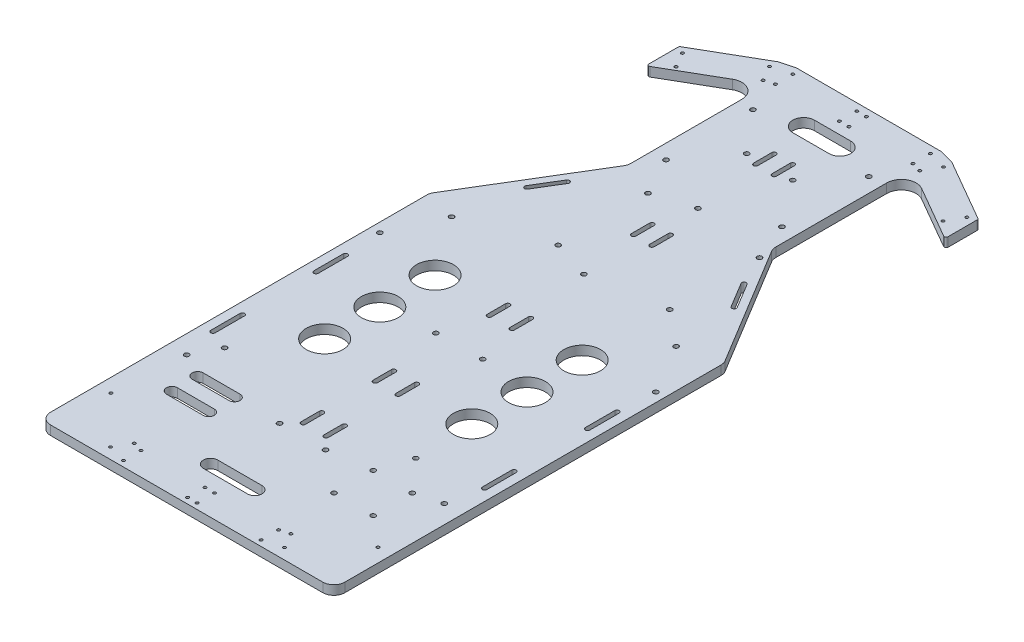
SolidWorks part; units mm, degrees
ref_plane "Front Plane" through (0, 0, 0) normal (0, 0, 1) x (1, 0, 0)
ref_plane "Top Plane" through (0, 0, 0) normal (0, 1, 0) x (1, 0, 0)
ref_plane "Right Plane" through (0, 0, 0) normal (1, 0, 0) x (0, 0, -1)
sketch "Sketch1" plane through (0, 0, 0) normal (0, 1, 0) x (1, 0, 0)
  line L0 (-3.559, 334.4007) -> (-3.559, -135.4993) construction
  line L1 (-53.658, 335.4416) -> (46.4133, 335.4416)
  line L2 (46.4133, 335.4416) -> (56.4133, 332.7622)
  line L3 (-105.159, -135.4993) -> (98.041, -135.4993)
  line L4 (99.7145, 307.7622) -> (99.7145, 284.6681)
  line L5 (-19.434, -135.4993) -> (-19.434, -55.4993) construction
  line L6 (-19.434, -55.4993) -> (12.316, -55.4993) construction
  line L7 (12.316, -55.4993) -> (12.316, -135.4993) construction
  line L8 (-19.434, -55.4993) -> (-19.434, 267.0007) construction
  line L9 (12.316, -55.4993) -> (12.316, 267.0007) construction
  line L10 (-53.5312, 315.4416) -> (-53.5312, 335.4416) construction
  line L11 (41.041, -51.3493) -> (68.041, -51.3493) construction
  line L12 (41.041, -51.3493) -> (41.041, -78.3493) construction
  line L13 (41.041, -78.3493) -> (68.041, -78.3493) construction
  line L14 (68.041, -51.3493) -> (68.041, -78.3493) construction
  line L15 (-92.459, -46.5993) -> (98.0409, -46.5993) construction
  line L16 (84.2181, -36.1058) -> (84.2181, 133.8942) construction
  line L17 (98.041, 133.8942) -> (-105.159, 133.8942) construction
  line L18 (48.441, -29.3238) -> (-83.559, -29.3238) construction
  line L19 (99.7145, 284.6681) -> (46.4133, 315.4416)
  line L20 (-0.259, 335.4416) -> (-0.259, 315.4416) construction
  line L21 (-106.8325, 307.7622) -> (-106.8325, 284.6681)
  line L22 (-53.5867, 219.1052) -> (-53.5867, 411.7781) construction
  line L23 (46.4133, 315.4416) -> (56.4133, 332.7622) construction
  line L24 (-105.159, 133.8942) -> (-53.5867, 219.1052)
  line L25 (46.4133, 219.1052) -> (98.041, 133.8942)
  line L26 (46.4133, 219.1052) -> (46.4133, 315.4416) construction
  line L27 (-83.559, -29.3238) -> (-83.559, 127.3942) construction
  line L28 (-75.3023, 127.3942) -> (-75.3023, 133.8942) construction
  line L29 (56.4133, 332.7622) -> (99.7145, 307.7622)
  line L30 (-83.559, 127.3942) -> (71.441, 127.3942) construction
  line L32 (-53.5312, 315.4416) -> (-63.5312, 332.7622) construction
  line L33 (-53.5312, 335.4416) -> (-63.5312, 332.7622)
  line L34 (-26.8485, 52.9803) -> (30.8308, 52.9803) construction
  line L35 (-63.5312, 332.7622) -> (-106.8325, 307.7622)
  line L36 (-105.159, 133.8942) -> (-105.159, -135.4993)
  line L37 (-6.859, 335.4416) -> (-6.859, 315.4416) construction
  line L38 (23.5928, 224.6027) -> (12.316, 224.6027) construction
  line L39 (-53.5312, 330.4416) -> (46.4133, 330.4416) construction
  line L40 (-29.8184, 209.2254) -> (-29.8184, 147.2254) construction
  line L41 (-29.8184, 147.2254) -> (47.1816, 147.2254) construction
  line L42 (47.1816, 147.2254) -> (47.1816, 209.2254) construction
  line L43 (-29.8184, 209.2254) -> (47.1816, 209.2254) construction
  line L44 (-53.5867, 219.1052) -> (46.4133, 219.1052) construction
  line L45 (-105.1532, 315.4416) -> (98.0468, 315.4416) construction
  line L46 (-53.658, 315.4416) -> (-53.658, 305.4416) construction
  line L47 (-53.5867, 305.4416) -> (46.4133, 305.4416) construction
  line L48 (-53.5867, 284.8828) -> (-43.5867, 284.8828) construction
  line L49 (-53.5312, 318.4416) -> (46.4133, 318.4416) construction
  line L50 (46.4133, 284.8828) -> (36.4133, 284.8828) construction
  line L51 (-51.0312, 335.4416) -> (-51.0312, 315.4416) construction
  line L52 (-53.5867, 219.1052) -> (-53.5867, 315.4416)
  line L53 (46.4133, 315.4416) -> (46.4133, 219.1052)
  line L54 (-53.658, 315.4416) -> (-53.658, 335.4416) construction
  line L55 (46.4133, 315.4416) -> (46.4133, 335.4416) construction
  line L56 (43.9133, 335.4416) -> (43.9133, 315.4416) construction
  line L57 (-105.159, 99.4507) -> (98.041, 99.4507) construction
  line L58 (-16.059, 302.9416) -> (8.941, 302.9416) construction
  line L59 (-16.059, 310.4416) -> (8.941, 310.4416)
  line L60 (-16.059, 295.4416) -> (8.941, 295.4416)
  line L61 (-9.923, 263.6917) -> (-9.909, 276.3916) construction
  line L62 (-11.423, 263.6933) -> (-11.409, 276.3933)
  line L63 (-8.423, 263.69) -> (-8.409, 276.39)
  line L64 (2.805, 263.6917) -> (2.791, 276.3916) construction
  line L65 (4.305, 263.6933) -> (4.291, 276.3933)
  line L66 (1.305, 263.69) -> (1.291, 276.39)
  line L67 (-11.433, 81.3437) -> (-11.433, 94.0437) construction
  line L68 (98.041, 133.8942) -> (98.041, -135.4993)
  line L69 (-12.957, 81.3437) -> (-12.957, 94.0437)
  line L70 (-9.909, 81.3437) -> (-9.909, 94.0437)
  line L71 (-9.909, 179.3877) -> (-9.909, 192.0877) construction
  line L72 (-11.433, 179.3877) -> (-11.433, 192.0877)
  line L73 (-8.385, 179.3877) -> (-8.385, 192.0877)
  line L74 (-11.433, 2.6037) -> (-11.433, 15.3037) construction
  line L75 (-12.957, 2.6037) -> (-12.957, 15.3037)
  line L76 (-9.909, 2.6037) -> (-9.909, 15.3037)
  line L77 (-11.433, -47.1803) -> (-11.433, -34.4803) construction
  line L78 (-12.957, -47.1803) -> (-12.957, -34.4803)
  line L79 (-9.909, -47.1803) -> (-9.909, -34.4803)
  line L80 (-97.285, 47.5342) -> (-97.285, 67.8542) construction
  line L81 (-98.809, 47.5342) -> (-98.809, 67.8542)
  line L82 (-95.761, 47.5342) -> (-95.761, 67.8542)
  line L83 (-18.799, -103.7493) -> (11.681, -103.7493) construction
  line L84 (-18.799, -98.7493) -> (11.681, -98.7493)
  line L85 (-18.799, -108.7493) -> (11.681, -108.7493)
  line L86 (4.315, -47.1803) -> (4.315, -34.4803) construction
  line L87 (5.839, -47.1803) -> (5.839, -34.4803)
  line L88 (2.791, -47.1803) -> (2.791, -34.4803)
  line L89 (4.315, 2.6037) -> (4.315, 15.3037) construction
  line L90 (5.839, 2.6037) -> (5.839, 15.3037)
  line L91 (2.791, 2.6037) -> (2.791, 15.3037)
  line L92 (4.315, 81.3437) -> (4.315, 94.0437) construction
  line L93 (5.839, 81.3437) -> (5.839, 94.0437)
  line L94 (2.791, 81.3437) -> (2.791, 94.0437)
  line L95 (2.791, 179.3877) -> (2.791, 192.0877) construction
  line L96 (4.315, 179.3877) -> (4.315, 192.0877)
  line L97 (1.267, 179.3877) -> (1.267, 192.0877)
  line L98 (-53.5867, 315.4416) -> (-106.8325, 284.6681)
  line L101 (-75.1227, 170.9222) -> (-64.6014, 188.3062) construction
  line L102 (-76.4265, 171.7113) -> (-65.9052, 189.0953)
  line L103 (-73.8189, 170.1331) -> (-63.2976, 187.5171)
  line L104 (68.0048, 170.9222) -> (57.4834, 188.3062) construction
  line L105 (69.3086, 171.7113) -> (58.7872, 189.0953)
  line L106 (66.701, 170.1331) -> (56.1796, 187.5171)
  line L110 (-75.949, -55.4893) -> (-50.549, -55.4893) construction
  line L111 (-75.949, -51.6793) -> (-50.549, -51.6793)
  line L112 (-75.949, -59.2993) -> (-50.549, -59.2993)
  line L113 (-75.949, -73.2693) -> (-50.549, -73.2693) construction
  line L114 (-75.949, -69.4593) -> (-50.549, -69.4593)
  line L115 (-75.949, -77.0793) -> (-50.549, -77.0793)
  line L116 (-97.285, -23.5858) -> (-97.285, -3.2658) construction
  line L117 (-98.809, -23.5858) -> (-98.809, -3.2658)
  line L118 (-95.761, -23.5858) -> (-95.761, -3.2658)
  line L119 (90.167, -23.5858) -> (90.167, -3.2658) construction
  line L120 (91.691, -23.5858) -> (91.691, -3.2658)
  line L121 (88.643, -23.5858) -> (88.643, -3.2658)
  line L122 (90.167, 47.5342) -> (90.167, 67.8542) construction
  line L123 (91.691, 47.5342) -> (91.691, 67.8542)
  line L124 (88.643, 47.5342) -> (88.643, 67.8542)
  circle A0 centre (-92.459, -46.5993) radius 1.651
  circle A1 centre (-19.434, -55.4993) radius 1.651
  circle A2 centre (12.316, -55.4993) radius 1.651
  circle A3 centre (-19.434, 267.0007) radius 1.651
  circle A4 centre (12.316, 267.0007) radius 1.651
  circle A5 centre (41.041, -51.3493) radius 1.651
  circle A6 centre (41.041, -78.3493) radius 1.651
  circle A7 centre (68.041, -78.3493) radius 1.651
  circle A8 centre (68.041, -51.3493) radius 1.651
  circle A9 centre (48.441, -29.3238) radius 1.651
  circle A10 centre (-83.559, -29.3238) radius 1.651
  circle A11 centre (-98.809, 93.1007) radius 1.651
  circle A12 centre (-3.559, 138.7138) radius 1.651
  circle A13 centre (-83.559, 127.3942) radius 1.651
  circle A14 centre (71.441, 127.3942) radius 1.651
  circle A15 centre (-19.434, 52.3942) radius 1.651
  circle A16 centre (12.316, 52.9803) radius 1.651
  circle A17 centre (91.6909, 93.1007) radius 1.651
  circle A18 centre (-29.8184, 209.2254) radius 1.651
  circle A19 centre (-29.8184, 147.2254) radius 1.651
  circle A20 centre (47.1816, 147.2254) radius 1.651
  circle A21 centre (47.1816, 209.2254) radius 1.651
  circle A22 centre (-43.5809, 295.4416) radius 1.651
  circle A23 centre (36.4191, 295.4416) radius 1.651
  circle A24 centre (-43.5532, 235.4416) radius 1.651
  circle A25 centre (36.441, 235.4416) radius 1.651
  circle A26 centre (85.341, -46.5993) radius 1.651
  circle A27 centre (-51.0312, 330.4416) radius 1
  circle A28 centre (-51.0312, 318.4416) radius 1
  circle A29 centre (43.9191, 330.4416) radius 1
  circle A30 centre (43.9133, 318.4416) radius 1
  circle A31 centre (-6.859, 330.4416) radius 1
  circle A32 centre (-0.259, 330.4416) radius 1
  circle A33 centre (-6.859, 318.4416) radius 1
  circle A34 centre (-0.259, 318.4416) radius 1
  circle A35 centre (56.5114, 326.932) radius 1
  circle A36 centre (50.5114, 316.5397) radius 1
  circle A37 centre (94.6165, 304.932) radius 1
  circle A38 centre (88.6165, 294.5397) radius 1
  circle A39 centre (-95.7344, 294.5397) radius 1
  circle A40 centre (-57.6293, 316.5397) radius 1
  circle A41 centre (-63.6293, 326.932) radius 1
  circle A42 centre (-101.7344, 304.932) radius 1
  circle A43 centre (88.6165, -95.6383) radius 1
  circle A44 centre (-54.359, 86.7507) radius 12.7
  circle A45 centre (50.5114, -117.6383) radius 1
  circle A46 centre (56.5114, -128.0307) radius 1
  circle A47 centre (-95.7344, -95.6383) radius 1
  circle A48 centre (-54.359, 48.6507) radius 12.7
  circle A49 centre (-57.6293, -117.6383) radius 1
  circle A50 centre (-63.6293, -128.0307) radius 1
  circle A51 centre (43.9133, -119.5403) radius 1
  circle A52 centre (43.9191, -131.5403) radius 1
  circle A53 centre (-0.259, -119.5403) radius 1
  circle A54 centre (-0.259, -131.5403) radius 1
  circle A55 centre (-6.859, -119.5403) radius 1
  circle A56 centre (-6.859, -131.5403) radius 1
  circle A57 centre (-51.0312, -119.5403) radius 1
  circle A58 centre (-51.0312, -131.5403) radius 1
  arc A59 (-16.059, 310.4416) -> (-16.059, 295.4416) centre (-16.059, 302.9416) ccw
  arc A60 (8.941, 295.4416) -> (8.941, 310.4416) centre (8.941, 302.9416) ccw
  arc A61 (-11.423, 263.6933) -> (-8.423, 263.69) centre (-9.923, 263.6917) ccw
  arc A62 (-8.409, 276.39) -> (-11.409, 276.3933) centre (-9.909, 276.3916) ccw
  arc A63 (4.305, 263.6933) -> (1.305, 263.69) centre (2.805, 263.6917) cw
  arc A64 (1.291, 276.39) -> (4.291, 276.3933) centre (2.791, 276.3916) cw
  arc A65 (-12.957, 81.3437) -> (-9.909, 81.3437) centre (-11.433, 81.3437) ccw
  arc A66 (-9.909, 94.0437) -> (-12.957, 94.0437) centre (-11.433, 94.0437) ccw
  arc A67 (-11.433, 179.3877) -> (-8.385, 179.3877) centre (-9.909, 179.3877) ccw
  arc A68 (-8.385, 192.0877) -> (-11.433, 192.0877) centre (-9.909, 192.0877) ccw
  arc A69 (-12.957, 2.6037) -> (-9.909, 2.6037) centre (-11.433, 2.6037) ccw
  arc A70 (-9.909, 15.3037) -> (-12.957, 15.3037) centre (-11.433, 15.3037) ccw
  arc A71 (-12.957, -47.1803) -> (-9.909, -47.1803) centre (-11.433, -47.1803) ccw
  arc A72 (-9.909, -34.4803) -> (-12.957, -34.4803) centre (-11.433, -34.4803) ccw
  circle A73 centre (-54.359, 10.5507) radius 12.7
  circle A74 centre (47.241, 10.5507) radius 12.7
  arc A75 (-18.799, -98.7493) -> (-18.799, -108.7493) centre (-18.799, -103.7493) ccw
  arc A76 (11.681, -108.7493) -> (11.681, -98.7493) centre (11.681, -103.7493) ccw
  arc A77 (5.839, -47.1803) -> (2.791, -47.1803) centre (4.315, -47.1803) cw
  arc A78 (2.791, -34.4803) -> (5.839, -34.4803) centre (4.315, -34.4803) cw
  arc A79 (5.839, 2.6037) -> (2.791, 2.6037) centre (4.315, 2.6037) cw
  arc A80 (2.791, 15.3037) -> (5.839, 15.3037) centre (4.315, 15.3037) cw
  arc A81 (5.839, 81.3437) -> (2.791, 81.3437) centre (4.315, 81.3437) cw
  arc A82 (2.791, 94.0437) -> (5.839, 94.0437) centre (4.315, 94.0437) cw
  arc A83 (4.315, 179.3877) -> (1.267, 179.3877) centre (2.791, 179.3877) cw
  arc A84 (1.267, 192.0877) -> (4.315, 192.0877) centre (2.791, 192.0877) cw
  circle A85 centre (-3.559, 217.4538) radius 1.651
  arc A87 (-76.4265, 171.7113) -> (-73.8189, 170.1331) centre (-75.1227, 170.9222) ccw
  arc A88 (-63.2976, 187.5171) -> (-65.9052, 189.0953) centre (-64.6014, 188.3062) ccw
  arc A89 (69.3086, 171.7113) -> (66.701, 170.1331) centre (68.0048, 170.9222) cw
  arc A90 (56.1796, 187.5171) -> (58.7872, 189.0953) centre (57.4834, 188.3062) cw
  arc A93 (-75.949, -51.6793) -> (-75.949, -59.2993) centre (-75.949, -55.4893) ccw
  arc A94 (-50.549, -59.2993) -> (-50.549, -51.6793) centre (-50.549, -55.4893) ccw
  arc A95 (-75.949, -69.4593) -> (-75.949, -77.0793) centre (-75.949, -73.2693) ccw
  arc A96 (-50.549, -77.0793) -> (-50.549, -69.4593) centre (-50.549, -73.2693) ccw
  circle A97 centre (47.241, 48.6507) radius 12.7
  circle A98 centre (47.241, 86.7507) radius 12.7
  arc A99 (-98.809, 47.5342) -> (-95.761, 47.5342) centre (-97.285, 47.5342) ccw
  arc A100 (-95.761, 67.8542) -> (-98.809, 67.8542) centre (-97.285, 67.8542) ccw
  arc A101 (-98.809, -23.5858) -> (-95.761, -23.5858) centre (-97.285, -23.5858) ccw
  arc A102 (-95.761, -3.2658) -> (-98.809, -3.2658) centre (-97.285, -3.2658) ccw
  arc A103 (91.691, -23.5858) -> (88.643, -23.5858) centre (90.167, -23.5858) cw
  arc A104 (88.643, -3.2658) -> (91.691, -3.2658) centre (90.167, -3.2658) cw
  arc A105 (91.691, 47.5342) -> (88.643, 47.5342) centre (90.167, 47.5342) cw
  arc A106 (88.643, 67.8542) -> (91.691, 67.8542) centre (90.167, 67.8542) cw
  point P50 (-0.9865, 223.8799)
  point P124 (-101.7344, 304.932)
  point P177 (-3.559, 302.9416)
  point P182 (-9.916, 270.0416)
  point P193 (2.798, 270.0416)
  point P199 (-11.433, 87.6937)
  point P206 (-9.909, 185.7377)
  point P213 (-11.433, 8.9537)
  point P220 (-11.433, -40.8303)
  point P236 (-3.559, -103.7493)
  point P241 (-9.909, 193.6117)
  point P242 (-9.9246, 262.1917)
  point P243 (-11.433, 95.5677)
  point P244 (-11.433, -32.9563)
  point P248 (4.315, -40.8303)
  point P255 (4.315, 8.9537)
  point P262 (4.315, 87.6937)
  point P269 (2.791, 185.7377)
  point P278 (-69.862, 179.6142)
  point P287 (62.7441, 179.6142)
  point P301 (-63.249, -55.4893)
  point P308 (-63.249, -73.2693)
  point P313 (-63.249, -59.2993)
  point P314 (-79.759, -73.2693)
  point P315 (-79.759, -55.4893)
  point P317 (-97.285, 57.6942)
  point P324 (-97.285, -13.4258)
  point P333 (90.167, -13.4258)
  point P340 (90.167, 57.6942)
  dimension "D3" = 3.302
  dimension "D10" = 3.302
  dimension "D11" = 3.302
  dimension "D14" = 3.302
  dimension "D15" = 3.302
  dimension "D20" = 3.302
  dimension "D21" = 3.302
  dimension "D22" = 3.302
  dimension "D23" = 3.302
  dimension "D26" = 3.302
  dimension "D27" = 75
  dimension "D30" = 3.302
  dimension "D32" = 3.302
  dimension "D33" = 60
  dimension "D34" = 3.302
  dimension "D35" = 9.8798
  dimension "D39" = 3.302
  dimension "D43" = 3.302
  dimension "D41" = 3.302
  dimension "D44" = 3.302
  dimension "D45" = 3.302
  dimension "D48" = 3.302
  dimension "D49" = 30
  dimension "D52" = 3.302
  dimension "D54" = 3.302
  dimension "D56" = 3.302
  dimension "D58" = 3.302
  dimension "D62" = 3.302
  dimension "D63" = 10
  dimension "D65" = 3.302
  dimension "D66" = 3.302
  dimension "D67" = 3.302
  dimension "D69" = 100.0713
  dimension "D68" = 469.9
  dimension "D75" = 15.875
  dimension "D77" = 26.2595
  dimension "D47" = 0
  dimension "D50" = 274.2131
  dimension "D51" = 139.7
  dimension "D28" = 139.7
  dimension "D46" = 12.7
  dimension "D57" = 88.9
  dimension "D78" = 60
  dimension "D72" = 10
  dimension "D73" = 10
  dimension "D74" = 60
  dimension "D79" = 9.9722
  dimension "D80" = 3.3
  dimension "D88" = 2
  dimension "D89" = 2
  dimension "D90" = 2
  dimension "D91" = 2
  dimension "D92" = 2
  dimension "D93" = 2
  dimension "D94" = 2
  dimension "D95" = 2
  dimension "D97" = 12.5
  dimension "D98" = 44.1722
  dimension "D100" = 2
  dimension "D101" = 2
  dimension "D102" = 2
  dimension "D103" = 2
  dimension "D104" = 25
  dimension "D118" = 3.048
  dimension "D124" = 66.04
  dimension "D126" = 3.048
  dimension "D140" = 25.4
  dimension "D145" = 50.8
  dimension "D146" = 269.3935
  dimension "D147" = 50.8
  dimension "D149" = 5
  dimension "D151" = 3
  dimension "D152" = 3
  dimension "D153" = 44
  dimension "D154" = 44
  dimension "D148" = 50.8
  dimension "D157" = 25.4
  dimension "D158" = 25.4
  dimension "D159" = 25.4
  dimension "D36" = 3.302
  dimension "D136" = 78.74
  dimension "D1" = 203.2
  dimension "D4" = 88.9
  dimension "D8" = 80
  dimension "D9" = 80
  dimension "D12" = 322.5
  dimension "D13" = 322.5
  dimension "D16" = 57.15
  dimension "D17" = 27
  dimension "D18" = 50
  dimension "D19" = 27
  dimension "D24" = 6.5
  dimension "D25" = 170
  dimension "D29" = 132
  dimension "D31" = 3.3
  dimension "D37" = 100
  dimension "D38" = 156.718
  dimension "D40" = 6.5
  dimension "D42" = 155
  dimension "D53" = 62
  dimension "D55" = 77
  dimension "D59" = 10
  dimension "D60" = 20
  dimension "D61" = 10
  dimension "D64" = 10
  dimension "D70" = 20
  dimension "D71" = 234.95
  dimension "D76" = 15.875
  dimension "D81" = 12.6999
  dimension "D82" = 6.3501
  dimension "D83" = 30.0001
  dimension "D84" = 5
  dimension "D85" = 3
  dimension "D86" = 2.5
  dimension "D87" = 2.5
  dimension "D96" = 25
  dimension "D99" = 15
  dimension "D105" = 12.7
  dimension "D106" = 6.35
  dimension "D107" = 3
  dimension "D108" = 25.4
  dimension "D109" = 31.75
  dimension "D110" = 10
  dimension "D111" = 15.24
  dimension "D112" = 30.48
  dimension "D113" = 6.35
  dimension "D114" = 3.048
  dimension "D115" = 12.7
  dimension "D116" = 68.58
  dimension "D117" = 6.35
  dimension "D119" = 12.7
  dimension "D120" = 83.82
  dimension "D121" = 6.35
  dimension "D122" = 3.048
  dimension "D123" = 12.7
  dimension "D125" = 6.35
  dimension "D127" = 12.7
  dimension "D128" = 35.56
  dimension "D129" = 5
  dimension "D130" = 203.2
  dimension "D131" = 96.3364
  dimension "D132" = 3.048
  dimension "D133" = 20.32
  dimension "D134" = 96.3364
  dimension "D135" = 45.72
  dimension "D137" = 7.62
  dimension "D138" = 7.62
  dimension "D139" = 10.16
  dimension "D141" = 25.4
  dimension "D142" = 25.4
  dimension "D143" = 25.4
  dimension "D144" = 58.42
  dimension "D150" = 5
  dimension "D155" = 3
  dimension "D156" = 3
  dimension "D160" = 12.7
  dimension "D161" = 38.1
  dimension "D162" = 38.1
  dimension "D163" = 76.2
  dimension "D164" = 20.32
  dimension "D165" = 3.048
  dimension "D166" = 6.35
  dimension "D167" = 3.048
  dimension "D168" = 6.35
  dimension "D169" = 20.32
  dimension "D170" = 71.12
extrude "Boss-Extrude1" add sketch "Sketch1" along normal blind 6.35
fillet "Fillet1" radius 7.62 6 edges at (98.041, 3.175, 135.4993) (-105.159, 3.175, 135.4993) (-105.159, 3.175, -133.8942) (98.041, 3.175, -133.8942) (46.4133, 3.175, -219.1052) (-53.5867, 3.175, -219.1052)
fillet "Fillet2" radius 1.27 8 edges at (56.4133, 3.175, -332.7622) (46.4133, 3.175, -335.4416) (-53.5312, 3.175, -335.4416) (-63.5312, 3.175, -332.7622) (99.7145, 3.175, -307.7622) (99.7145, 3.175, -284.6681) (-106.8325, 3.175, -284.6681) (-106.8325, 3.175, -307.7622)
fillet "Fillet3" radius 10.16 2 edges at (46.4133, 3.175, -315.4416) (-53.5867, 3.175, -315.4416)
